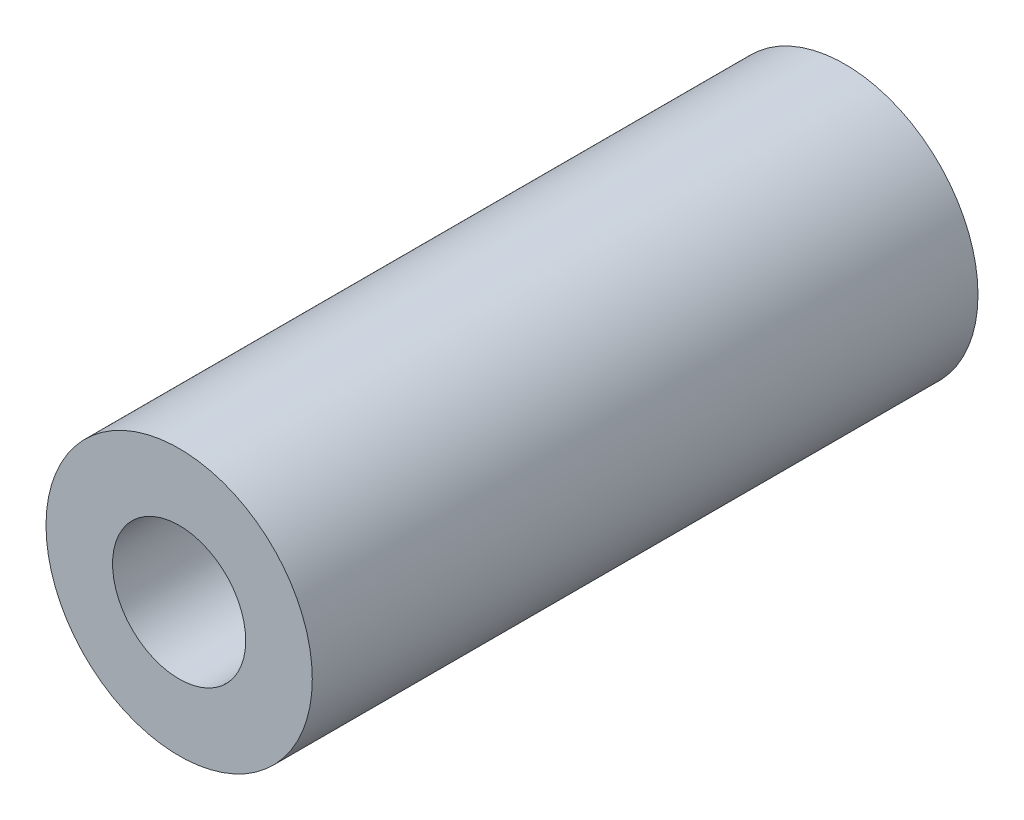
SolidWorks part; units mm, degrees
ref_plane "Front Plane" through (0, 0, 0) normal (0, 0, 1) x (1, 0, 0)
ref_plane "Top Plane" through (0, 0, 0) normal (0, 1, 0) x (1, 0, 0)
ref_plane "Right Plane" through (0, 0, 0) normal (1, 0, 0) x (0, 0, -1)
sketch "Sketch1" plane through (0, 0, 0) normal (0, 0, 1) x (1, 0, 0)
  circle A0 centre (0, 0) radius 1.5875
  circle A1 centre (0, 0) radius 3.175
  dimension "D1" = 3.175
  dimension "D2" = 6.35
extrude "Boss-Extrude1" add sketch "Sketch1" along normal blind 15.875
